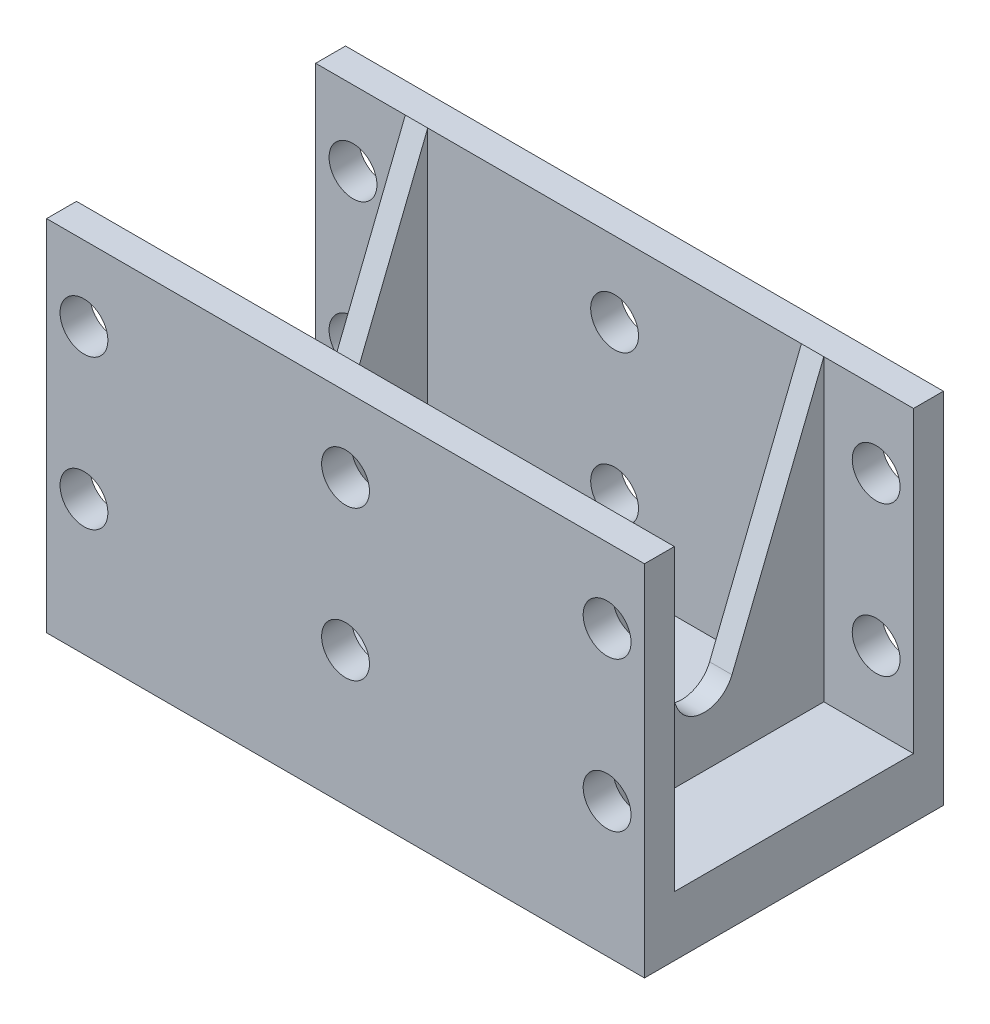
SolidWorks part; units mm, degrees
ref_plane "Front Plane" through (0, 0, 0) normal (0, 0, 1) x (1, 0, 0)
ref_plane "Top Plane" through (0, 0, 0) normal (0, 1, 0) x (1, 0, 0)
ref_plane "Right Plane" through (0, 0, 0) normal (1, 0, 0) x (0, 0, -1)
sketch "Sketch1" plane through (0, 0, 0) normal (0, 1, 0) x (1, 0, 0)
  line L1 (-12.5, 4.8) -> (12.5, 4.8)
  line L2 (-12.5, 4.8) -> (-12.5, -4.8)
  line L3 (-12.5, -4.8) -> (12.5, -4.8)
  line L4 (12.5, 4.8) -> (12.5, -4.8)
  line L5 (-12.5, 4.8) -> (12.5, -4.8) construction
  line L6 (-12.5, -4.8) -> (12.5, 4.8) construction
  point P0 (0, 0)
  dimension "D1" = 25
  dimension "D2" = 9.6
extrude "Boss-Extrude1" add sketch "Sketch1" along normal blind 2
sketch "Sketch3" plane through (0, 2, 0) normal (0, 1, 0) x (1, 0, 0)
  line L0 (-7, 0) -> (7, 0) construction
  circle A0 centre (-7, 0) radius 2.3
  circle A1 centre (7, 0) radius 2.3
  point P8 (0, 0)
  dimension "D2" = 4.6
  dimension "D1" = 14
extrude "Cut-Extrude1" cut sketch "Sketch3" against normal through all
sketch "Sketch4" plane through (0, 0, 0) normal (0, 1, 0) x (1, 0, 0)
  line L5 (-10.1, 3.1) -> (10.1, 3.1)
  line L6 (-10.1, 3.1) -> (-10.1, -3.1)
  line L11 (-10.1, -3.1) -> (10.1, -3.1)
  line L12 (10.1, 3.1) -> (10.1, -3.1)
  line L13 (-10.1, 3.1) -> (10.1, -3.1) construction
  line L14 (-10.1, -3.1) -> (10.1, 3.1) construction
  point P0 (0, 0)
  dimension "D1" = 6.2
  dimension "D2" = 20.2
extrude "Cut-Extrude2" cut sketch "Sketch4" along normal blind 0.27 contours L5 L12 L11 L6
sketch "Sketch5" plane through (0, 2, 0) normal (0, 1, 0) x (1, 0, 0)
  line L1 (-20, 10) -> (20, 10)
  line L2 (-20, 10) -> (-20, -10)
  line L3 (-20, -10) -> (20, -10)
  line L4 (20, 10) -> (20, -10)
  line L5 (-20, 10) -> (20, -10) construction
  line L6 (-20, -10) -> (20, 10) construction
  point P0 (0, 0)
  dimension "D1" = 40
  dimension "D2" = 20
extrude "Boss-Extrude2" add sketch "Sketch5" along normal blind 4
hole_wizard "M3 Clearance Hole1" positions "Sketch6" profile "Sketch7" hole size "M3" standard "ANSI Metric" end condition through all
sketch "Sketch6" plane through (0, 2, 0) normal (0, -1, 0) x (-1, 0, 0)
  circle A0 centre (7, 0) radius 2.3 construction
  circle A1 centre (-7, 0) radius 2.3 construction
  point P0 (-7, 0)
  point P2 (7, 0)
  point P5 (0, 0)
  point P6 (0, 0)
  point P9 (0, 0)
  point P12 (0, 0)
sketch "Sketch7" plane through (7, 2, 0) normal (1, 0, 0) x (0, 0, -1)
  line L0 (0, 0) -> (0, 4)
  line L1 (0, 4) -> (1.6, 4)
  line L2 (1.6, 4) -> (1.6, 0)
  line L5 (1.6, 0) -> (0, 0)
  line L11 (0, -6.35) -> (0, 107.95) construction
  dimension "Thru Hole Dia." = 3.2
  dimension "Thru Hole Depth" = 4
sketch "Sketch9" plane through (0, 6, 0) normal (0, 1, 0) x (1, 0, 0)
  line L0 (20, -10) -> (20, 10) construction
  line L1 (-20, 10) -> (20, 10)
  line L2 (-20, 10) -> (-20, 8)
  line L3 (-20, 8) -> (20, 8)
  line L4 (20, 10) -> (20, 8)
  line L5 (-20, 10) -> (20, 8) construction
  line L6 (-20, 8) -> (20, 10) construction
  line L7 (-20, 10) -> (-20, -10) construction
  line L8 (20, -10) -> (-20, -10)
  line L9 (20, -10) -> (20, -8)
  line L10 (20, -8) -> (-20, -8)
  line L11 (-20, -10) -> (-20, -8)
  line L12 (20, -10) -> (-20, -8) construction
  line L13 (20, -8) -> (-20, -10) construction
  point P4 (0, 9)
  point P12 (0, -9)
  dimension "D1" = 2
extrude "Boss-Extrude4" add sketch "Sketch9" along normal blind 20
ref_plane "Plane1" through (0, 0, 0) normal (-1, 0, 0) x (0, 0, 1)
ref_plane "Plane2" through (-12.5, 0, 0) normal (-1, 0, 0) x (0, 0, 1)
sketch "Sketch10" plane through (-12.5, 0, 0) normal (-1, 0, 0) x (0, 0, 1)
  line L0 (-10, 26) -> (-8, 26) construction
  line L1 (-10, 26) -> (-8, 26) construction
  line L2 (8, 26) -> (10, 26) construction
  line L3 (8, 26) -> (10, 26)
  line L5 (-8, 6) -> (0, 6)
  line L6 (-8, 26) -> (0, 6)
  line L7 (0, 6) -> (8, 26)
  line L8 (8, 6) -> (8, 26)
  line L10 (-8, 6) -> (-8, 26)
  line L11 (8, 6) -> (0, 6)
extrude "Boss-Extrude5" add sketch "Sketch10" along normal blind 1.5 contours L10 L5 L6 | L11 L8 L7
fillet "Fillet1" radius 2 1 edges at (-13.25, 6, 0)
mirror "Mirror1" about plane through (0, 0, 0) normal (-1, 0, 0) of "Fillet1", "Boss-Extrude5"
hole_wizard "M3 Clearance Hole2" positions "Sketch11" profile "Sketch12" hole size "M3" standard "ANSI Metric" end condition through all
sketch "Sketch11" plane through (0, 0, 10) normal (0, 0, 1) x (1, 0, 0)
  line L1 (-17.5, 21) -> (17.5, 21) construction
  line L2 (-17.5, 21) -> (-17.5, 11) construction
  line L3 (-17.5, 11) -> (17.5, 11) construction
  line L4 (17.5, 21) -> (17.5, 11) construction
  line L5 (-17.5, 21) -> (17.5, 11) construction
  line L6 (-17.5, 11) -> (17.5, 21) construction
  line L7 (0, 11) -> (0, -11) construction
  line L8 (-20, 26) -> (20, 26) construction
  point P0 (-17.5, 21)
  point P2 (17.5, 21)
  point P4 (17.5, 11)
  point P6 (-17.5, 11)
  point P90 (0, 21)
  point P91 (0, 11)
  dimension "D1" = 10
  dimension "D2" = 35
  dimension "D3" = 5
sketch "Sketch12" plane through (-17.5, 21, 10) normal (1, 0, 0) x (0, -1, 0)
  line L0 (0, 0) -> (0, 20)
  line L1 (0, 20) -> (1.6, 20)
  line L2 (1.6, 20) -> (1.6, 0)
  line L5 (1.6, 0) -> (0, 0)
  line L11 (0, -6.35) -> (0, 107.95) construction
  dimension "Thru Hole Dia." = 3.2
  dimension "Thru Hole Depth" = 20
